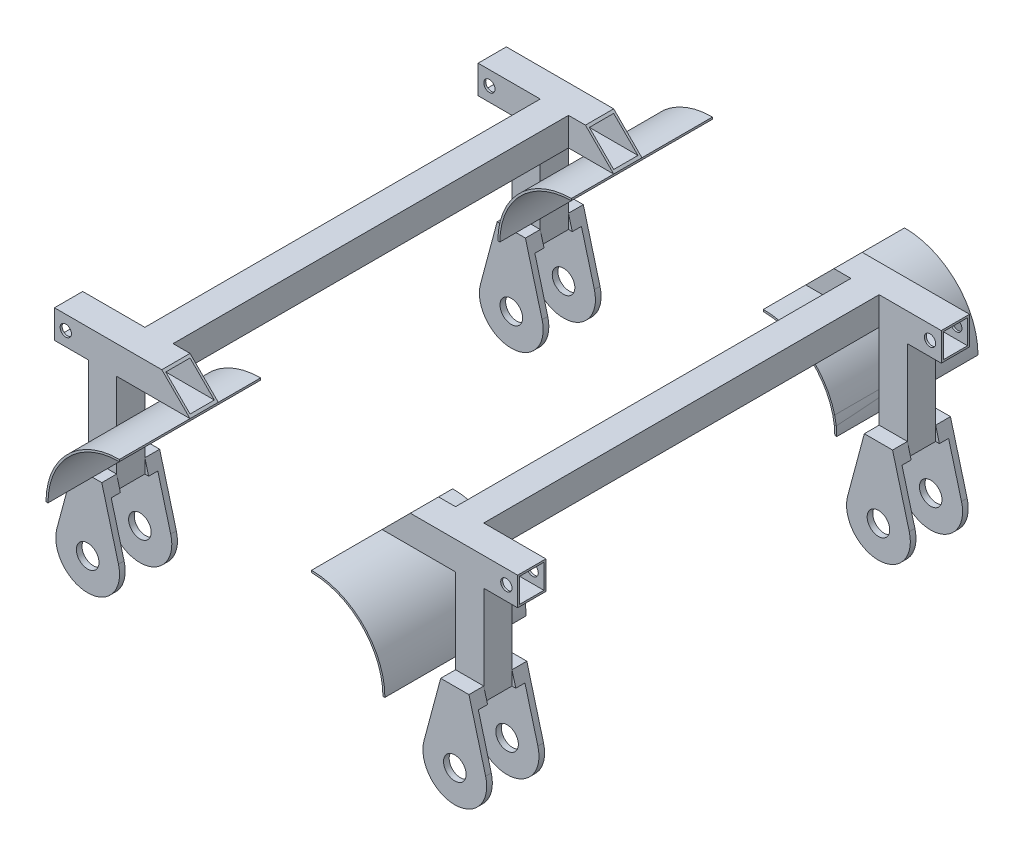
SolidWorks part; units mm, degrees
ref_plane "Front Plane" through (0, 0, 0) normal (0, 0, 1) x (1, 0, 0)
ref_plane "Top Plane" through (0, 0, 0) normal (0, 1, 0) x (1, 0, 0)
ref_plane "Right Plane" through (0, 0, 0) normal (1, 0, 0) x (0, 0, -1)
sketch "Sketch1" plane through (0, 0, 0) normal (0, 0, 1) x (1, 0, 0)
  line L0 (0, -11.2927) -> (0, 37.1736) construction
  line L1 (-5, 25) -> (5, 25)
  line L2 (-5, 25) -> (-10.9089, 2.9192)
  line L3 (5, 25) -> (10.9089, 2.9192)
  circle A0 centre (0, 0) radius 4
  arc A1 (-10.9089, 2.9192) -> (10.9089, 2.9192) centre (0, 0) ccw
  point P9 (0, 25)
  dimension "D1" = 8
  dimension "D2" = 5
  dimension "D3" = 25
extrude "Boss-Extrude1" add sketch "Sketch1" along normal blind 4 and the other way blind 1.25
sketch "Sketch2" plane through (0, 0, 4) normal (0, 0, 1) x (1, 0, 0)
  line L0 (-5, 55) -> (-5, 20)
  line L1 (-5, 20) -> (5, 20)
  line L2 (5, 20) -> (5, 55)
  line L3 (5, 55) -> (-5, 55)
  line L4 (5, 25) -> (-5, 25) construction
  dimension "D1" = 55
  dimension "D2" = 5
extrude "Boss-Extrude2" add sketch "Sketch2" along normal blind 10
ref_plane "Plane1" through (0, 0, 9) normal (0, 0, 1) x (1, 0, 0)
mirror "Mirror1" about plane through (0, 0, 9) normal (0, 0, 1) of bodies 102
ref_plane "Plane2" through (17, 0, 0) normal (1, 0, 0) x (0, 0, -1)
sketch "Sketch4" plane through (17, 0, 0) normal (1, 0, 0) x (0, 0, -1)
  line L0 (-13.3, 64.3) -> (-4.7, 64.3)
  line L1 (-14, 55) -> (-4, 55)
  line L2 (-14, 55) -> (-14, 65)
  line L3 (-14, 65) -> (-4, 65)
  line L4 (-4, 55) -> (-4, 65)
  line L5 (-4.7, 55.7) -> (-4.7, 64.3)
  line L6 (-13.3, 55.7) -> (-4.7, 55.7)
  line L7 (-13.3, 55.7) -> (-13.3, 64.3)
  dimension "D1" = 10
  dimension "D2" = 10
  dimension "D3" = 0.7
extrude "Boss-Extrude3" add sketch "Sketch4" against normal blind 48
sketch "Sketch5" plane through (0, 0, 14) normal (0, 0, 1) x (1, 0, 0)
  line L0 (17, -5.5) -> (17, 5.5) construction
  line L1 (5, 55) -> (17, 55) construction
  circle A0 centre (13, 60) radius 2
  dimension "D1" = 4
  dimension "D2" = 5
extrude "Cut-Extrude1" cut sketch "Sketch5" against normal blind 50
sketch "Sketch9" plane through (0, 0, 14) normal (0, 0, 1) x (1, 0, 0)
  line L0 (-5, 55) -> (-5, 25) construction
  line L1 (-31, 55) -> (-5, 55)
  line L2 (-31, 55) -> (-31, 54.3)
  line L3 (-5.7, 29) -> (-5, 29)
  line L4 (-5, 55) -> (-5, 29)
  arc A0 (-5, 29) -> (-31, 55) centre (-31, 29) ccw
  arc A1 (-5.7, 29) -> (-31, 54.3) centre (-31, 29) ccw
  circle A2 centre (-31, 29) radius 26 construction
  circle A3 centre (-31, 29) radius 25.3 construction
  dimension "D1" = 26
  dimension "D2" = 0.7
extrude "Boss-Extrude4" add sketch "Sketch9" along normal mid plane 50 separate body contours A1 L3 A0 L2
sketch "Sketch10" plane through (0, 0, 14) normal (0, 0, 1) x (1, 0, 0)
  line L0 (-31, 65) -> (-31, 55)
  line L1 (-31, 55) -> (-21, 65)
  line L2 (-31, 65) -> (17, 65) construction
  line L3 (-21, 65) -> (-31, 65)
extrude "Cut-Extrude2" cut sketch "Sketch10" against normal blind 50
ref_plane "Plane3" through (0, 0, -66) normal (0, 0, -1) x (-1, 0, 0)
mirror "Mirror2" about plane through (0, 0, -66) normal (0, 0, -1) of bodies 107 106
sketch "Sketch11" plane through (0, 0, -136) normal (0, 0, 1) x (1, 0, 0)
  line L0 (-21, 65) -> (17, 65) construction
  line L1 (-5, 55) -> (-15, 55)
  line L2 (-5, 55) -> (-5, 65)
  line L3 (-5, 65) -> (-15, 65)
  line L4 (-15, 55) -> (-15, 65)
  dimension "D1" = 10
extrude "Boss-Extrude5" add sketch "Sketch11" along normal up to vertex (140 mm away)
ref_plane "Plane4" through (-65, 0, 0) normal (-1, 0, 0) x (0, 0, 1)
mirror "Mirror7" about plane through (0, 0, -66) normal (0, 0, -1) of bodies 106
sketch "Sketch16" plane through (-5, 0, 0) normal (-1, 0, 0) x (0, 0, 1)
  line L1 (14, 20) -> (17.25, 20)
  line L2 (14, 20) -> (14, -13.7382)
  line L3 (14, -13.7382) -> (17.25, -13.7382)
  line L4 (17.25, 20) -> (17.25, -13.7382)
  line L5 (4, 20) -> (0.75, 20)
  line L6 (4, 20) -> (4, -15.9945)
  line L7 (4, -15.9945) -> (0.75, -15.9945)
  line L8 (0.75, 20) -> (0.75, -15.9945)
  dimension "D1" = 3.25
  dimension "D2" = 3.25
extrude "Cut-Extrude5" cut sketch "Sketch16" against normal blind 44 and the other way blind 36
mirror "Mirror8" about plane through (0, 0, -66) normal (0, 0, -1) of "Cut-Extrude5"
mirror "Mirror9" about plane through (-65, 0, 0) normal (-1, 0, 0) of bodies 121 106 119
